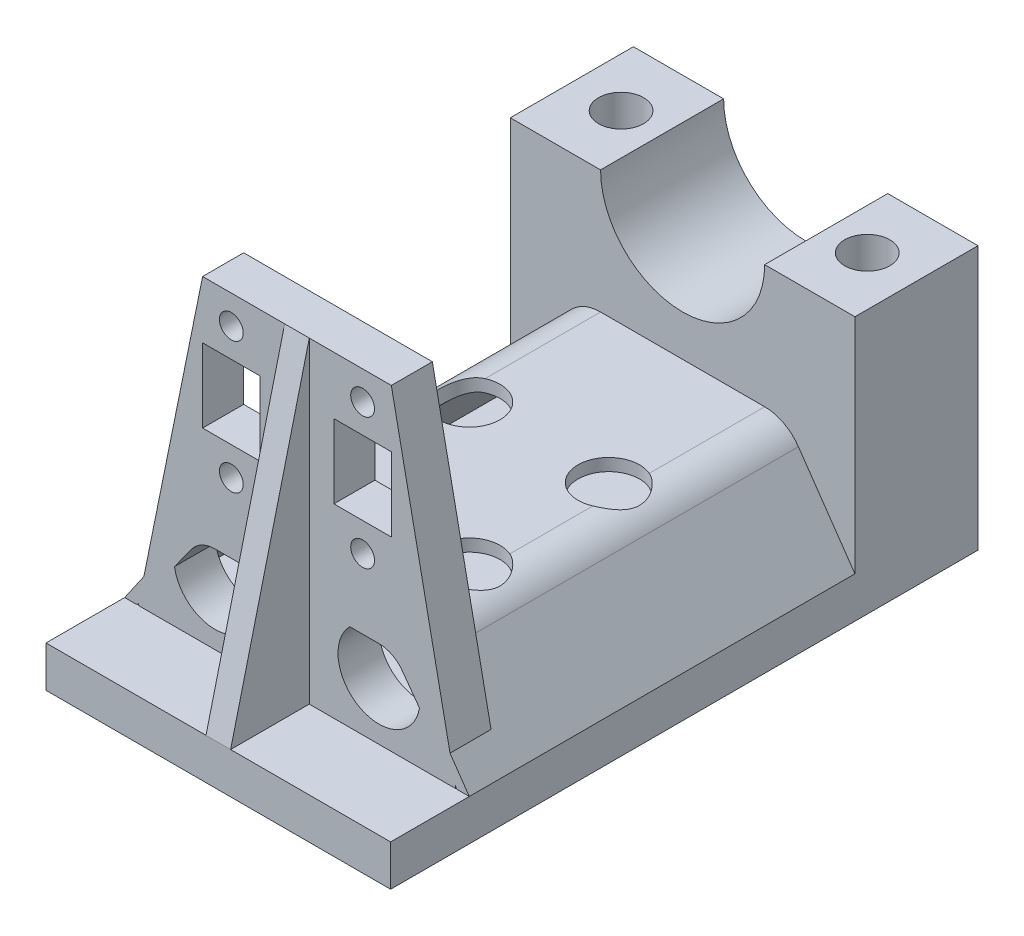
SolidWorks part; units mm, degrees
material "ABS"
ref_plane "Front Plane" through (0, 0, 0) normal (0, 0, 1) x (1, 0, 0)
ref_plane "Top Plane" through (0, 0, 0) normal (0, 1, 0) x (1, 0, 0)
ref_plane "Right Plane" through (0, 0, 0) normal (1, 0, 0) x (0, 0, -1)
sketch "Mouting Mount Sketch" plane through (0, 0, 0) normal (0, 0, 1) x (1, 0, 0)
  line L1 (25, -55) -> (-25, -55)
  line L2 (25, -55) -> (25, 0)
  line L3 (25, 0) -> (-25, 0)
  line L4 (-25, -55) -> (-25, 0)
  line L5 (25, -55) -> (-25, 0) construction
  line L6 (25, 0) -> (-25, -55) construction
  circle A0 centre (0, 0) radius 10
  point P3 (0, -27.5)
  dimension "D1" = 20
  dimension "D2" = 50
  dimension "D3" = 55
extrude "Motor Mount Solid" add sketch "Mouting Mount Sketch" along normal mid plane 15 contours A0 L3 L4 L1 L2
sketch "Encoder Distance Sketch" plane through (0, -55, 0) normal (0, -1, 0) x (1, 0, 0)
  line L0 (25, 7.5) -> (25, -7.5) construction
  line L1 (-25, 7.5) -> (25, 7.5)
  line L2 (-25, 7.5) -> (-25, 49.5)
  line L3 (-25, 49.5) -> (25, 49.5)
  line L4 (25, 7.5) -> (25, 49.5)
  line L5 (-25, -7.5) -> (25, -7.5) construction
  line L6 (-25, -7.5) -> (-25, 54.5) construction
  line L7 (-25, 54.5) -> (25, 54.5) construction
  line L8 (25, -7.5) -> (25, 54.5) construction
  line M9 (-25, -7.5) -> (25, -7.5)
  line M10 (25, -7.5) -> (25, 7.5)
  line M11 (25, 7.5) -> (-25, 7.5)
  line M12 (-25, 7.5) -> (-25, -7.5)
  dimension "D1" = 42
  dimension "D2" = 5
extrude "Encoder Distance Solid" add sketch "Encoder Distance Sketch" along normal blind 5 contours M12 M9 M10 M11 | L4 L3 L2 M11 | L3 L8 L7 L6
sketch "Encoder Mount Sketch" plane through (0, 0, 49.5) normal (0, 0, 1) x (1, 0, 0)
  line L0 (-25, -60) -> (-25, -55)
  line L1 (-8, -8) -> (8, -8) construction
  line L2 (-8, -8) -> (-8, 8) construction
  line L3 (-8, 8) -> (8, 8) construction
  line L4 (8, -8) -> (8, 8) construction
  line L5 (-8, -8) -> (8, 8) construction
  line L6 (-8, 8) -> (8, -8) construction
  line L7 (-11.5, -11.5) -> (11.5, -11.5) construction
  line L8 (-11.5, -11.5) -> (-11.5, 11.5) construction
  line L9 (-11.5, 11.5) -> (11.5, 11.5)
  line L10 (11.5, -11.5) -> (11.5, 11.5) construction
  line L11 (-11.5, -11.5) -> (11.5, 11.5) construction
  line L12 (-11.5, 11.5) -> (11.5, -11.5) construction
  line L13 (-11.5, 4.5) -> (-4.5, 4.5)
  line L14 (-11.5, 4.5) -> (-11.5, -4.5)
  line L15 (-11.5, -4.5) -> (-4.5, -4.5)
  line L16 (-4.5, 4.5) -> (-4.5, -4.5)
  line L17 (-11.5, 4.5) -> (-4.5, -4.5) construction
  line L18 (-11.5, -4.5) -> (-4.5, 4.5) construction
  line L19 (4.5, 4.5) -> (11.5, 4.5)
  line L20 (4.5, 4.5) -> (4.5, -4.5)
  line L21 (4.5, -4.5) -> (11.5, -4.5)
  line L22 (11.5, 4.5) -> (11.5, -4.5)
  line L23 (4.5, 4.5) -> (11.5, -4.5) construction
  line L24 (4.5, -4.5) -> (11.5, 4.5) construction
  line L25 (-25, -55) -> (-11.5, 11.5)
  line L26 (-25, -60) -> (25, -60)
  line L27 (25, -60) -> (25, -55)
  line L28 (25, -55) -> (11.5, 11.5)
  circle A0 centre (-8, 8) radius 1.45
  circle A1 centre (8, 8) radius 1.45
  circle A2 centre (-8, -8) radius 1.45
  circle A3 centre (8, -8) radius 1.45
  circle A4 centre (8, 8) radius 3.5 construction
  circle A5 centre (-8, 8) radius 3.5 construction
  circle A6 centre (-8, -8) radius 3.5 construction
  circle A7 centre (8, -8) radius 3.5 construction
  point P0 (0, 0)
  point P14 (0, 0)
  point P19 (-8, 0)
  point P24 (8, 0)
  dimension "D2" = 2.9
  dimension "D3" = 7
  dimension "D1" = 16
extrude "Encoder Mount Solid" add sketch "Encoder Mount Sketch" along normal blind 5
sketch "Motor Clamp Mounting Holes Sketch" plane through (0, 0, 0) normal (0, 1, 0) x (1, 0, 0)
  line L0 (-15, 0) -> (15, 0) construction
  circle A0 centre (-15, 0) radius 2.75
  circle A1 centre (15, 0) radius 2.75
  point P4 (0, 0)
  dimension "D2" = 5.5
  dimension "D1" = 30
extrude "Motor Clamp Mounting Holes Cut" cut sketch "Motor Clamp Mounting Holes Sketch" against normal through all both and the other way through all
sketch "Gusset Plate Sketch" plane through (0, 0, 54.5) normal (0, 0, 1) x (1, 0, 0)
  line L1 (-25, -55) -> (25, -55)
  line L2 (-25, -55) -> (-25, -60)
  line L3 (-25, -60) -> (25, -60)
  line L4 (25, -55) -> (25, -60)
extrude "Gusset Plate Solid" add sketch "Gusset Plate Sketch" along normal blind 16.5
sketch "Gusset Sketch" plane through (0, 0, 0) normal (1, 0, 0) x (0, 0, -1)
  line L0 (-54.5, 11.5) -> (-71, -55)
  line L1 (-71, -55) -> (-54.5, -55)
  line L2 (-54.5, -55) -> (-54.5, 11.5)
extrude "Gusset Solid" add sketch "Gusset Sketch" along normal mid plane 3
sketch "Mounting Plate Sketch" plane through (0, -55, 0) normal (0, 1, 0) x (1, 0, 0)
  line L0 (25, -7.5) -> (25, -49.5) construction
  line L1 (-25, -71) -> (25, -71)
  line L2 (-25, -71) -> (-25, 21)
  line L3 (-25, 21) -> (25, 21)
  line L4 (25, -71) -> (25, 21)
  line L5 (-19, -65) -> (19, -65) construction
  line L6 (-19, 15) -> (19, 15) construction
  circle A0 centre (-19, -65) radius 2.65
  circle A1 centre (19, -65) radius 6 construction
  circle A2 centre (19, -65) radius 2.65
  circle A3 centre (-19, -65) radius 6 construction
  circle A4 centre (-19, 15) radius 6 construction
  circle A5 centre (19, 15) radius 6 construction
  circle A6 centre (-19, 15) radius 2.65
  circle A7 centre (19, 15) radius 2.65
  point P10 (0, -65)
  point P18 (0, 15)
  dimension "D1" = 12
  dimension "D2" = 5.3
  dimension "D3" = 80
extrude "Mounting Plate Solid" add sketch "Mounting Plate Sketch" against normal up to surface (5 mm away) up to face at (-17.75, -60, 0)
sketch "Mounting Hole Sketch" plane through (0, -55, 0) normal (0, 1, 0) x (1, 0, 0)
  line L0 (25, 21) -> (25, -71) construction
  line L3 (25, -25) -> (-25, -25) construction
  line L4 (-25, -49.5) -> (-25, -7.5) construction
  circle A0 centre (-19, 15) radius 2.65
  circle A1 centre (19, 15) radius 2.65
  circle A3 centre (19, -65) radius 2.65
  circle A4 centre (-19, -65) radius 2.65
  circle A5 centre (-19, 15) radius 2.65 construction
extrude "Mounting Holes Cut" cut sketch "Mounting Hole Sketch" against normal through all both and the other way through all contours A3 | A4 | A1 | A0
sketch "Mounting Plate Trim Sketch" plane through (0, -55, 0) normal (0, 1, 0) x (1, 0, 0)
  line L1 (-25, 21) -> (25, 21)
  line L2 (-25, 21) -> (-25, 7.5)
  line L3 (-25, 7.5) -> (25, 7.5)
  line L4 (25, 21) -> (25, 7.5)
  line L5 (-25, -7.5) -> (25, -7.5)
  line L6 (-25, -7.5) -> (-25, -49.5)
  line L7 (-25, -49.5) -> (25, -49.5)
  line L8 (25, -7.5) -> (25, -49.5)
  line L9 (1.5, -54.5) -> (25, -54.5)
  line L10 (1.5, -54.5) -> (1.5, -71)
  line L11 (1.5, -71) -> (25, -71)
  line L12 (25, -54.5) -> (25, -71)
  line L13 (-1.5, -54.5) -> (-25, -54.5)
  line L14 (-1.5, -54.5) -> (-1.5, -71)
  line L15 (-1.5, -71) -> (-25, -71)
  line L16 (-25, -54.5) -> (-25, -71)
extrude "Mounting Plate Trim Cut" cut sketch "Mounting Plate Trim Sketch" against normal blind 2
sketch "Sketch2" plane through (0, 0, -7.5) normal (0, 0, -1) x (-1, 0, 0)
  line L1 (-21, -27.1363) -> (21, -27.1363)
  line L2 (-21, -27.1363) -> (-21, 27.1363)
  line L3 (-21, 27.1363) -> (21, 27.1363)
  line L4 (21, -27.1363) -> (21, 27.1363)
  line L5 (-21, -27.1363) -> (21, 27.1363) construction
  line L6 (-21, 27.1363) -> (21, -27.1363) construction
  line L7 (25, 60) -> (-25, 60)
  line L8 (25, 60) -> (25, -60)
  line L9 (25, -60) -> (-25, -60)
  line L10 (-25, 60) -> (-25, -60)
  line L11 (25, 60) -> (-25, -60) construction
  line L12 (25, -60) -> (-25, 60) construction
  point P0 (0, 0)
  point P7 (0, 0)
  dimension "D1" = 42
  dimension "D2" = 27.1363
extrude "Cut-Extrude1" cut sketch "Sketch2" against normal through all both and the other way through all
sketch "Sketch3" plane through (0, -27.1363, 0) normal (0, -1, 0) x (1, 0, 0)
  line L0 (21, 7.5) -> (21, -7.5) construction
  line L1 (-21, -7.5) -> (21, -7.5)
  line L2 (-21, -7.5) -> (-21, 64.0865)
  line L3 (-21, 64.0865) -> (21, 64.0865)
  line L4 (21, -7.5) -> (21, 64.0865)
  line L5 (-21, -7.5) -> (21, -7.5) construction
  line L6 (1.5, 64.0865) -> (-1.5, 64.0865) construction
extrude "Boss-Extrude1" add sketch "Sketch3" along normal blind 5
sketch "Sketch4" plane through (0, -27.1363, 0) normal (0, 1, 0) x (1, 0, 0)
  line L0 (21, -7.5) -> (21, -64.0865) construction
  line L1 (-21, -7.5) -> (21, -7.5) construction
  line L2 (-21, -7.5) -> (-21, -49.5) construction
  line L3 (-21, -49.5) -> (21, -49.5) construction
  line L4 (21, -7.5) -> (21, -49.5) construction
  line L5 (19.3435, -49.5) -> (-19.3435, -49.5) construction
  line L8 (-8.5, -42) -> (8.5, -42) construction
  line L9 (-8.5, -42) -> (-8.5, -25) construction
  line L10 (-8.5, -25) -> (8.5, -25) construction
  line L11 (8.5, -42) -> (8.5, -25) construction
  line L12 (-8.5, -42) -> (8.5, -25) construction
  line L13 (-8.5, -25) -> (8.5, -42) construction
  circle A0 centre (8.5, -25) radius 5 construction
  circle A1 centre (-8.5, -25) radius 5 construction
  circle A2 centre (-8.5, -42) radius 5 construction
  circle A3 centre (8.5, -42) radius 5 construction
  circle A4 centre (-8.5, -25) radius 2.15
  circle A5 centre (8.5, -25) radius 2.15
  circle A6 centre (-8.5, -42) radius 2.15
  circle A7 centre (8.5, -42) radius 2.15
  point P9 (0, -33.5)
  dimension "D1" = 10
  dimension "D4" = 4.3
  dimension "D2" = 17
  dimension "D3" = 17
  dimension "D5" = 16
extrude "Cut-Extrude2" cut sketch "Sketch4" against normal through all both and the other way through all contours A5 | A4
sketch "Sketch5" plane through (0, 0, 54.5) normal (0, 0, 1) x (1, 0, 0)
  line L0 (-10, -20) -> (10, -20) construction
  circle A0 centre (-10, -20) radius 5
  circle A1 centre (10, -20) radius 5
  point P3 (0, -20)
  dimension "D1" = 10
  dimension "D2" = 20
  dimension "D3" = 20
extrude "Cut-Extrude3" cut sketch "Sketch5" against normal through all both
sketch "Sketch6" plane through (0, 0, -7.5) normal (0, 0, -1) x (-1, 0, 0)
  line L0 (21, -27.1363) -> (-21, -27.1363) construction
  line L1 (21, -27.1363) -> (19.5, -27.1363)
  line L2 (-21, -27.1363) -> (-14.1152, -17.16)
  line L3 (21, -27.1363) -> (14.1152, -17.16)
  line L5 (-10, -15) -> (10, -15)
  line L6 (-10, -16.5) -> (10, -16.5)
  line L7 (-19.5, -27.1363) -> (-12.8806, -18.012)
  line L8 (19.5, -27.1363) -> (12.8806, -18.012)
  line L9 (-19.5, -27.1363) -> (-21, -27.1363)
  circle A0 centre (-10, -20) radius 5 construction
  circle A1 centre (10, -20) radius 5 construction
  arc A2 (-10, -15) -> (-14.1152, -17.16) centre (-10, -20) ccw
  arc A3 (14.1152, -17.16) -> (10, -15) centre (10, -20) ccw
  arc A5 (-10, -16.5) -> (-12.8806, -18.012) centre (-10, -20) ccw
  arc A6 (12.8806, -18.012) -> (10, -16.5) centre (10, -20) ccw
  point P18 (0, 0)
  dimension "D1" = 1.5
  dimension "D2" = 1.5
  dimension "D3" = 1.5
  dimension "D4" = 1.5
  dimension "D5" = 1.5
extrude "Boss-Extrude4" add sketch "Sketch6" against normal up to surface (62 mm away) contours L1 L8 A6 L6 A5 L7 L9 L2 A2 L5 A3 L3 up to face at (15, -20, 54.5)
sketch "Sketch7" plane through (0, -32.1363, 0) normal (0, -1, 0) x (1, 0, 0)
  circle A0 centre (8.5, 42) radius 2.15 construction
  circle A1 centre (-8.5, 42) radius 2.15 construction
  circle A2 centre (-8.5, 25) radius 2.15 construction
  circle A3 centre (8.5, 25) radius 2.15 construction
  circle A4 centre (8.5, 42) radius 2.15
  circle A5 centre (-8.5, 42) radius 2.15
  circle A6 centre (-8.5, 25) radius 2.15
  circle A7 centre (8.5, 25) radius 2.15
  circle A8 centre (-8.5, 42) radius 3.75
  circle A9 centre (8.5, 42) radius 3.75
  circle A10 centre (8.5, 25) radius 3.75
  circle A11 centre (-8.5, 25) radius 3.75
  dimension "D1" = 7.5
extrude "Cut-Extrude5" cut sketch "Sketch7" against normal up to surface (17.1363 mm away) contours A8 | A9 | A10 | A11 up to face at (0, -15, 28.5)
